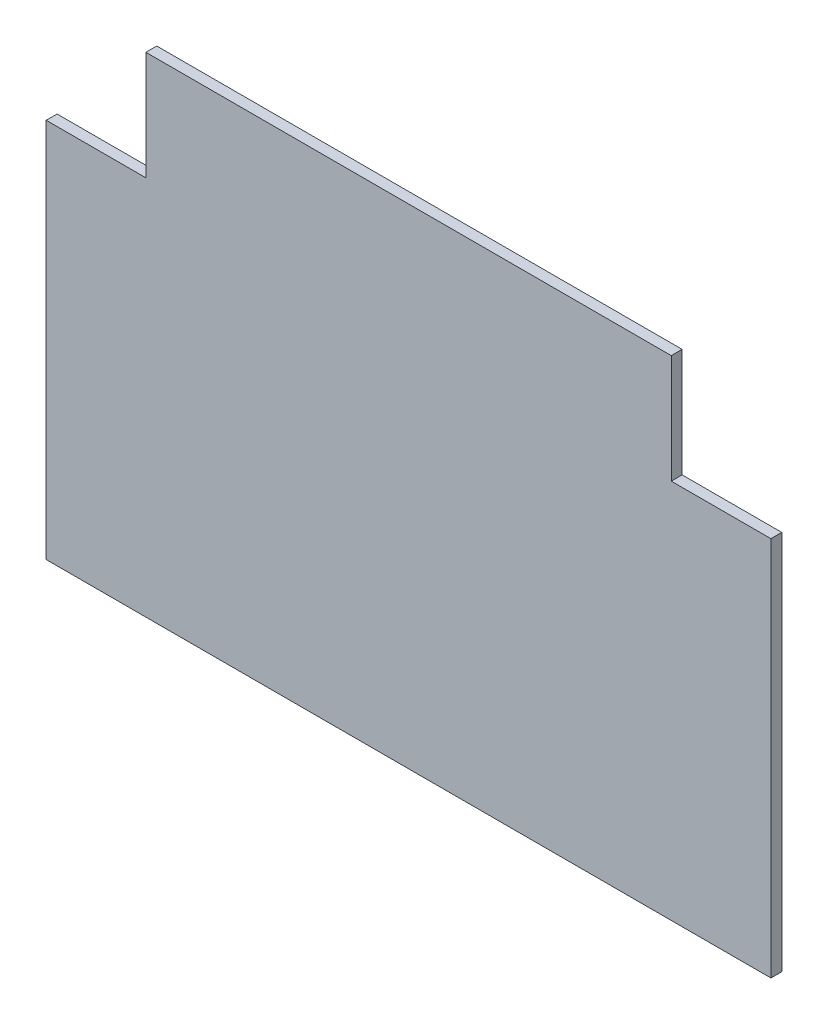
SolidWorks part; units mm, degrees
material "Pine"
ref_plane "Front Plane" through (0, 0, 0) normal (0, 0, 1) x (1, 0, 0)
ref_plane "Top Plane" through (0, 0, 0) normal (0, 1, 0) x (1, 0, 0)
ref_plane "Right Plane" through (0, 0, 0) normal (1, 0, 0) x (0, 0, -1)
sketch "Sketch1" plane through (0, 0, 0) normal (0, 0, 1) x (1, 0, 0)
  line L1 (-110.8686, 260.6668) -> (289.1314, 260.6668)
  line L2 (-110.8686, 260.6668) -> (-110.8686, -9.3332)
  line L3 (-110.8686, -9.3332) -> (289.1314, -9.3332)
  line L4 (289.1314, 260.6668) -> (289.1314, -9.3332)
  dimension "D1" = 400
  dimension "D2" = 270
extrude "Boss-Extrude1" add sketch "Sketch1" along normal blind 6
sketch "Sketch2" plane through (0, 0, 0) normal (0, 0, -1) x (-1, 0, 0)
  line L1 (-289.1314, 200.6668) -> (-234.1314, 200.6668)
  line L2 (-289.1314, 200.6668) -> (-289.1314, 260.6668)
  line L3 (-289.1314, 260.6668) -> (-234.1314, 260.6668)
  line L4 (-234.1314, 200.6668) -> (-234.1314, 260.6668)
  line L5 (110.8686, 200.6668) -> (55.8686, 200.6668)
  line L6 (110.8686, 200.6668) -> (110.8686, 260.6668)
  line L7 (110.8686, 260.6668) -> (55.8686, 260.6668)
  line L8 (55.8686, 200.6668) -> (55.8686, 260.6668)
  line L9 (110.8686, 260.6668) -> (110.8686, -9.3332) construction
  line L10 (-289.1314, 260.6668) -> (110.8686, 260.6668) construction
  line L11 (-289.1314, -9.3332) -> (-289.1314, 260.6668) construction
  dimension "D1" = 55
  dimension "D2" = 55
  dimension "D3" = 60
  dimension "D4" = 60
  dimension "D5" = 0
  dimension "D6" = 0
  dimension "D7" = 0
  dimension "D8" = 0
extrude "Cut-Extrude1" cut sketch "Sketch2" against normal blind 40
